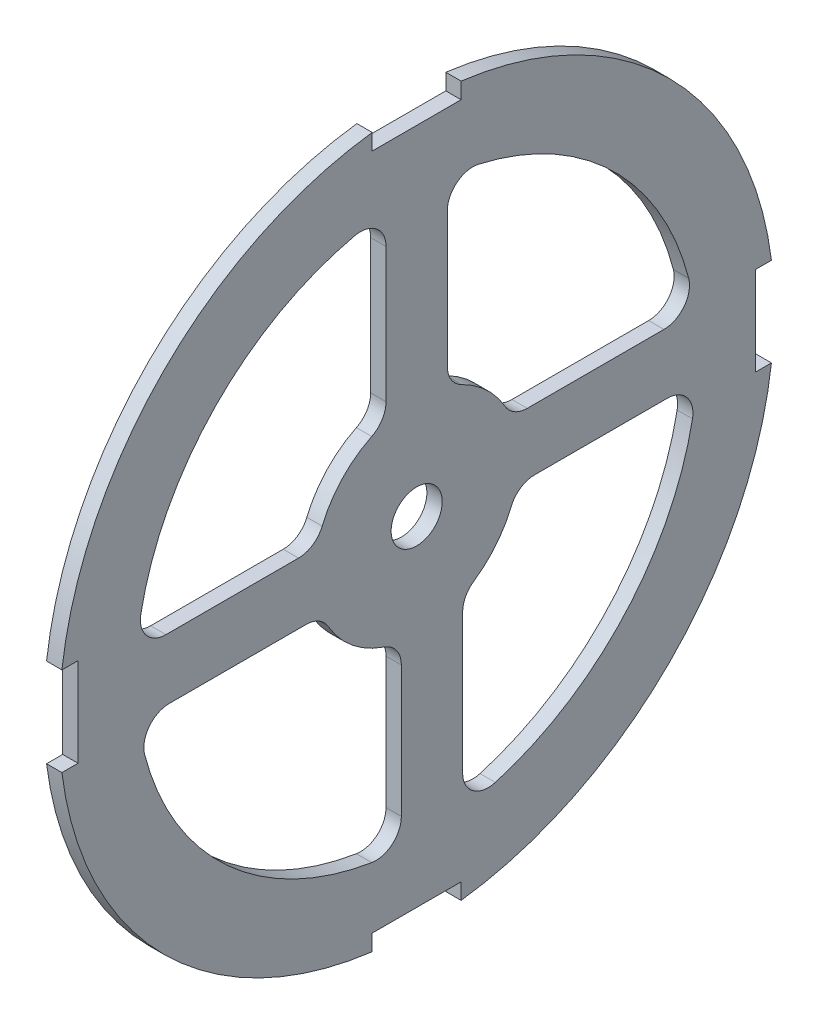
SolidWorks part; units mm, degrees
material "AISI 304"
ref_plane "Front Plane" through (0, 0, 0) normal (0, 0, 1) x (1, 0, 0)
ref_plane "Top Plane" through (0, 0, 0) normal (0, 1, 0) x (1, 0, 0)
ref_plane "Right Plane" through (0, 0, 0) normal (1, 0, 0) x (0, 0, -1)
sketch "Sketch1" plane through (0, 0, 0) normal (1, 0, 0) x (0, 0, -1)
  line L5 (0, 0) -> (0, 35) construction
  line L22 (-34.7286, 4.35) -> (-33.15, 4.35)
  line L23 (-33.15, 4.35) -> (-33.15, -4.35)
  line L47 (-34.7286, -4.35) -> (-33.15, -4.35)
  line L55 (-4.35, -34.7286) -> (-4.35, -33.15)
  line L56 (-4.35, -33.15) -> (4.35, -33.15)
  line L57 (4.35, -34.7286) -> (4.35, -33.15)
  line L61 (4.35, 34.7286) -> (4.35, 33.15)
  line L62 (4.35, 33.15) -> (-4.35, 33.15)
  line L63 (-4.35, 34.7286) -> (-4.35, 33.15)
  line L64 (34.7286, -4.35) -> (33.15, -4.35)
  line L65 (33.15, -4.35) -> (33.15, 4.35)
  line L66 (34.7286, 4.35) -> (33.15, 4.35)
  line L67 (9.2702, 3.75) -> (27.2431, 3.75)
  line L69 (-3, 9.5394) -> (-3, 27.3359)
  line L74 (3, 9.5394) -> (3, 27.3359)
  line L77 (9.7436, -2.25) -> (27.4078, -2.25)
  line L78 (4.5, -8.9303) -> (4.5, -27.1293)
  line L79 (-1.5, -9.8869) -> (-1.5, -27.4591)
  line L80 (-9.2702, -3.75) -> (-27.2431, -3.75)
  line L81 (-9.7436, 2.25) -> (-27.4078, 2.25)
  circle A1 centre (0, 0) radius 2.5
  circle A2 centre (0, 0) radius 40 construction
  arc A7 (4.35, -34.7286) -> (34.7286, -4.35) centre (0, 0) ccw
  arc A8 (34.7286, 4.35) -> (4.35, 34.7286) centre (0, 0) ccw
  arc A9 (-4.35, 34.7286) -> (-34.7286, 4.35) centre (0, 0) ccw
  arc A10 (-34.7286, -4.35) -> (-4.35, -34.7286) centre (0, 0) ccw
  arc A11 (27.2431, 3.75) -> (3, 27.3359) centre (0, 0) ccw
  arc A12 (-3, 9.5394) -> (-9.7436, 2.25) centre (0, 0) ccw
  arc A13 (9.2702, 3.75) -> (3, 9.5394) centre (0, 0) ccw
  arc A14 (4.5, -8.9303) -> (9.7436, -2.25) centre (0, 0) ccw
  arc A15 (4.5, -27.1293) -> (27.4078, -2.25) centre (0, 0) ccw
  arc A16 (-3, 27.3359) -> (-27.4078, 2.25) centre (0, 0) ccw
  arc A17 (-27.2431, -3.75) -> (-1.5, -27.4591) centre (0, 0) ccw
  arc A18 (-9.2702, -3.75) -> (-1.5, -9.8869) centre (0, 0) ccw
  point P8 (0, 18.6707)
  point P27 (0, 0)
  point P31 (0, 0)
  point P38 (0, 0)
  point P52 (0.75, 0)
  dimension "D6" = 5
  dimension "D7" = 3
  dimension "D5" = 80
  dimension "D1" = 70
  dimension "D8" = 55
  dimension "D9" = 20
  dimension "D2" = 4
  dimension "D3" = 8.7
  dimension "D4" = 4.35
  dimension "D10" = 6
  dimension "D11" = 4
extrude "Boss-Extrude3" add sketch "Sketch1" along normal blind 1.5
fillet "Fillet1" radius 2.5 16 edges at (0.75, -2.25, -27.4078) (0.75, -27.1293, -4.5) (0.75, -27.4591, 1.5) (0.75, -3.75, 27.2431) (0.75, -2.25, -9.7436) (0.75, -8.9303, -4.5) (0.75, -3.75, 9.2702) (0.75, -9.8869, 1.5) (0.75, 27.3359, 3) (0.75, 2.25, 27.4078) (0.75, 2.25, 9.7436) (0.75, 9.5394, 3) (0.75, 9.5394, -3) (0.75, 3.75, -9.2702) (0.75, 3.75, -27.2431) (0.75, 27.3359, -3)
